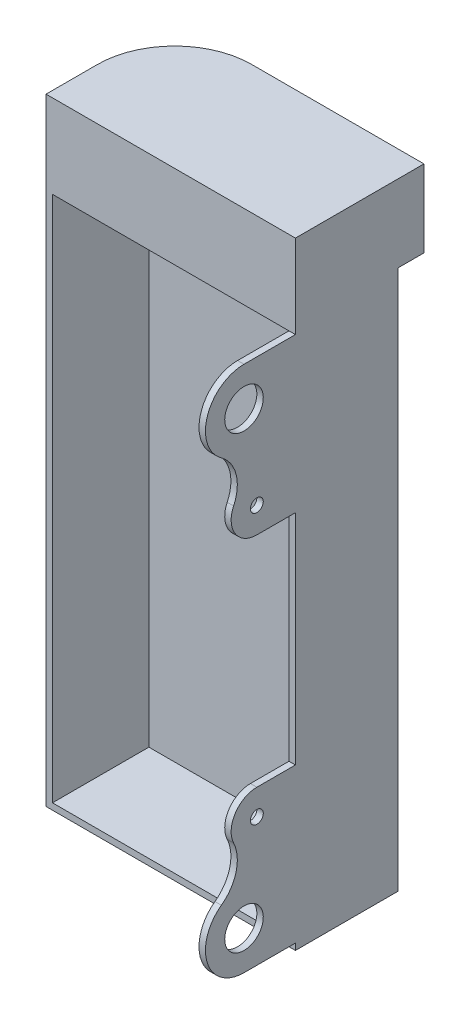
SolidWorks part; units mm, degrees
ref_plane "Front Plane" through (0, 0, 0) normal (0, 0, 1) x (1, 0, 0)
ref_plane "Top Plane" through (0, 0, 0) normal (0, 1, 0) x (1, 0, 0)
ref_plane "Right Plane" through (0, 0, 0) normal (1, 0, 0) x (0, 0, -1)
sketch "Sketch1" plane through (0, 0, 0) normal (0, 0, 1) x (1, 0, 0)
  line L0 (55, 0) -> (-55, 0) construction
  line L1 (-61.595, 133.35) -> (61.595, 133.35)
  line L2 (-61.595, 133.35) -> (-61.595, -133.35)
  line L3 (-61.595, -133.35) -> (61.595, -133.35)
  line L4 (61.595, 133.35) -> (61.595, -133.35)
  line L5 (0, -55) -> (0, 55) construction
  dimension "D1" = 123.19
  dimension "D2" = 266.7
  dimension "D3" = 133.35
  dimension "D4" = 61.595
extrude "Boss-Extrude1" add sketch "Sketch1" along normal mid plane 50.8
shell "Shell1" thickness 3.175
sketch "Sketch2" plane through (58.42, 0, 0) normal (-1, 0, 0) x (0, 0, 1)
  line L0 (50.8, 130.175) -> (25.4, 130.175)
  line L1 (44.45, 53.975) -> (25.4, 53.975)
  line L2 (25.4, 133.35) -> (25.4, -133.35) construction
  line L3 (25.4, 130.175) -> (25.4, 53.975)
  line L5 (25.4, 133.35) -> (-25.4, 133.35) construction
  arc A0 (61.9722, 95.695) -> (50.8, 130.175) centre (50.8, 111.125) ccw
  arc A1 (44.45, 53.975) -> (55.9278, 72.111) centre (44.45, 66.675) ccw
  arc A2 (61.9722, 95.695) -> (55.9278, 72.111) centre (73.1445, 80.2651) ccw
  circle A3 centre (50.8, 111.125) radius 9.525
  circle A4 centre (44.45, 66.675) radius 3.175
  dimension "D2" = 12.7
  dimension "D3" = 19.05
  dimension "D4" = 19.05
  dimension "D7" = 19.05
  dimension "D8" = 6.35
  dimension "D1" = 76.2
  dimension "D5" = 25.4
  dimension "D6" = 19.05
  dimension "D9" = 3.175
extrude "Boss-Extrude2" add sketch "Sketch2" against normal up to surface (3.175 mm away) up to face at (61.595, 0, 0)
sketch "Sketch3" plane through (0, 133.35, 0) normal (0, 1, 0) x (1, 0, 0)
  line L7 (-61.595, -25.4) -> (61.595, -25.4)
  line L8 (-61.595, -25.4) -> (-61.595, 0)
  line L9 (-23.495, 38.1) -> (61.595, 38.1)
  line L10 (61.595, -25.4) -> (61.595, 38.1)
  arc A2 (-61.595, 0) -> (-23.495, 38.1) centre (-23.495, 0) cw
  point P5 (0, 0)
  dimension "D1" = 25.4
  dimension "D2" = 63.5
extrude "Boss-Extrude3" add sketch "Sketch3" along normal blind 38.1
mirror "Mirror1" about plane through (0, 0, 0) normal (0, 1, 0) of "Boss-Extrude2"
equation "\"D3@Sketch1\"=\"D2@Sketch1\"/2"
equation "\"D4@Sketch1\"=\"D1@Sketch1\"/2"
